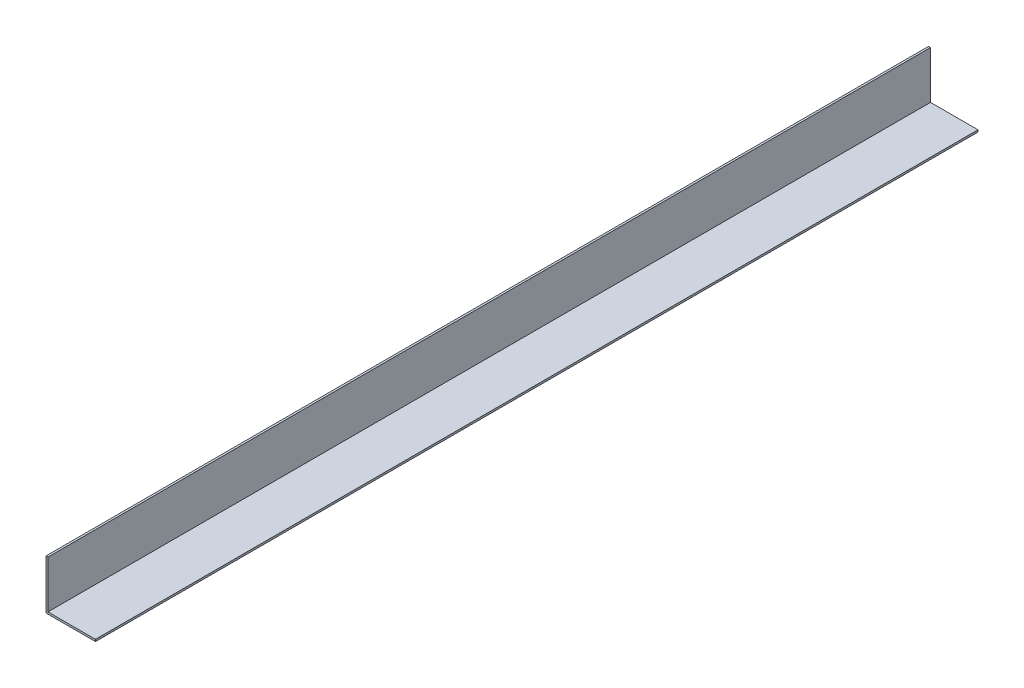
SolidWorks part; units mm, degrees
ref_plane "Front Plane" through (0, 0, 0) normal (0, 0, 1) x (1, 0, 0)
ref_plane "Top Plane" through (0, 0, 0) normal (0, 1, 0) x (1, 0, 0)
ref_plane "Right Plane" through (0, 0, 0) normal (1, 0, 0) x (0, 0, -1)
sketch "Sketch1" plane through (0, 0, 0) normal (0, 0, 1) x (1, 0, 0)
  line L0 (0, 30) -> (0, 0)
  line L1 (0, 0) -> (30, 0)
  line L2 (30, 0) -> (30, 1.2)
  line L3 (30, 1.2) -> (1.2, 1.2)
  line L4 (1.2, 1.2) -> (1.2, 30)
  line L5 (1.2, 30) -> (0, 30)
  dimension "D1" = 30
  dimension "D2" = 1.2
extrude "Boss-Extrude1" add sketch "Sketch1" along normal mid plane 535
